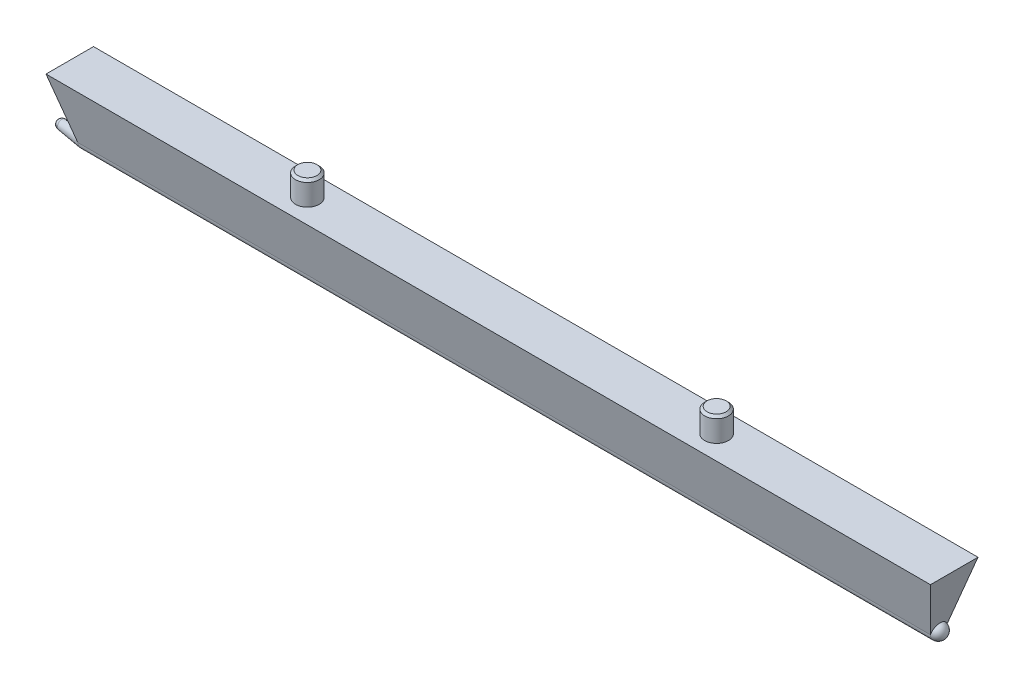
SolidWorks part; units mm, degrees
ref_plane "Front Plane" through (0, 0, 0) normal (0, 0, 1) x (1, 0, 0)
ref_plane "Top Plane" through (0, 0, 0) normal (0, 1, 0) x (1, 0, 0)
ref_plane "Right Plane" through (0, 0, 0) normal (1, 0, 0) x (0, 0, -1)
sketch "Sketch1" plane through (0, 0, 0) normal (0, 1, 0) x (1, 0, 0)
  line L0 (0, 0) -> (0, 20)
  line L1 (0, 20) -> (744.4, 20)
  line L2 (744.4, 20) -> (744.4, -20)
  line L3 (744.4, -20) -> (0, -20)
  line L4 (0, -20) -> (0, 0)
  dimension "D1" = 20
  dimension "D2" = 20
  dimension "D3" = 744.4
extrude "Boss-Extrude1" add sketch "Sketch1" against normal blind 50 draft 15 contours L1 L2 L3 L4 L0
ref_plane "Plane1" through (731.0025, 0, 0) normal (1, 0, 0) x (0, 0, -1)
sketch "Sketch3" plane through (731.0025, 0, 0) normal (1, 0, 0) x (0, 0, -1)
  line L0 (6.6025, -50) -> (-6.6025, -50) construction
  circle A0 centre (0, -50) radius 6.6025
extrude "Boss-Extrude2" add sketch "Sketch3" against normal up to vertex (717.6051 mm away)
sketch "Sketch4" plane through (13.3975, 0, 0) normal (-1, 0, 0) x (0, 0, 1)
  circle A1 centre (0, -50) radius 6.6025
extrude "Boss-Extrude3" add sketch "Sketch4" along normal blind 20 draft 8 separate body contours A1
sketch "Sketch6" plane through (-6.6025, 0, 0) normal (-1, 0, 0) x (0, 0, 1)
  line L0 (3.7917, -50) -> (-3.7917, -50)
  line L1 (-3.7917, -50) -> (3.7917, -50)
  circle A0 centre (0, -50) radius 3.7917 construction
  arc A1 (3.7917, -50) -> (-3.7917, -50) centre (0, -50) cw
revolve "Revolve2" add sketch "Sketch6" angle 360 about L0
sketch "Sketch7" plane through (731.0025, 0, 0) normal (1, 0, 0) x (0, 0, -1)
  line L1 (-6.6025, -50) -> (6.6025, -50)
  arc A1 (6.6025, -50) -> (-6.6025, -50) centre (0, -50) cw
sketch "Sketch8" plane through (731.0025, 0, 0) normal (1, 0, 0) x (0, 0, -1)
  line L0 (6.6025, -50) -> (-6.6025, -50)
  arc A0 (-6.6025, -50) -> (6.6025, -50) centre (0, -50) ccw
  arc A1 (-6.6025, -50) -> (6.6025, -50) centre (0, -50) ccw construction
revolve "Revolve3" add sketch "Sketch8" angle 360 about L1
sketch "Sketch9" plane through (0, 0, 0) normal (0, 1, 0) x (1, 0, 0)
  line L0 (0, 0) -> (200, 0)
  line L1 (744.4, 0) -> (544.4, 0)
  line L2 (744.4, 20) -> (744.4, -20) construction
  line L3 (200, 0) -> (544.4, 0)
  circle A2 centre (200, 0) radius 10
  circle A3 centre (544.4, 0) radius 10
  dimension "D2" = 20
  dimension "D4" = 20
  dimension "D1" = 200
  dimension "D3" = 344.4
extrude "Boss-Extrude4" add sketch "Sketch9" along normal blind 20
chamfer "Chamfer1" distance 2 angle 45 2 edges at (544.4, 20, 10) (200, 20, 10)
